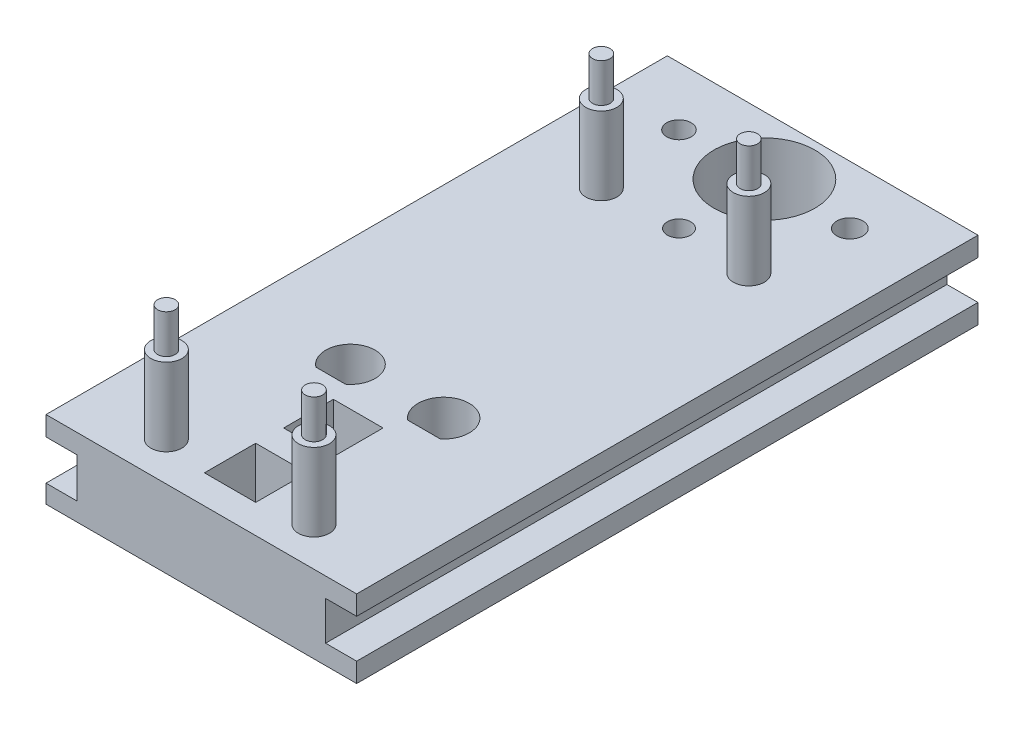
SolidWorks part; units mm, degrees
ref_plane "Plan de face" through (0, 0, 0) normal (0, 0, 1) x (1, 0, 0)
ref_plane "Plan de dessus" through (0, 0, 0) normal (0, 1, 0) x (1, 0, 0)
ref_plane "Plan de droite" through (0, 0, 0) normal (1, 0, 0) x (0, 0, -1)
sketch "Esquisse2" plane through (0, 0, 0) normal (0, 1, 0) x (1, 0, 0)
  line L1 (-20, 40) -> (20, 40)
  line L2 (-20, 40) -> (-20, -40)
  line L3 (-20, -40) -> (20, -40)
  line L4 (20, 40) -> (20, -40)
  line L5 (-20, 40) -> (20, -40) construction
  line L6 (-20, -40) -> (20, 40) construction
  point P0 (0, 0)
  dimension "D1" = 80
  dimension "D2" = 40
extrude "Boss.-Extru.1" add sketch "Esquisse2" along normal blind 10
sketch "Esquisse3" plane through (0, 10, 0) normal (0, 1, 0) x (1, 0, 0)
  line L2 (-20, -40) -> (20, -40) construction
  circle A0 centre (9.5, -35) radius 2
  circle A1 centre (9.5, 21) radius 2
  circle A2 centre (-9.5, -35) radius 2
  circle A3 centre (-9.5, 21) radius 2
  dimension "D3" = 4
  dimension "D5" = 4
  dimension "D7" = 4
  dimension "D8" = 4
  dimension "D1" = 9.5
  dimension "D2" = 5
  dimension "D4" = 56
  dimension "D6" = 19
extrude "Boss.-Extru.2" add sketch "Esquisse3" along normal blind 10
sketch "Esquisse4" plane through (0, 20, 0) normal (0, 1, 0) x (1, 0, 0)
  circle A0 centre (-9.5, -35) radius 1.125
  circle A1 centre (-9.5, -35) radius 2 construction
  circle A2 centre (9.5, -35) radius 1.125
  circle A3 centre (9.5, -35) radius 2 construction
  circle A4 centre (-9.5, 21) radius 1.125
  circle A5 centre (-9.5, 21) radius 2 construction
  circle A6 centre (9.5, 21) radius 1.125
  circle A7 centre (9.5, 21) radius 2 construction
  dimension "D2" = 2.25
  dimension "D3" = 2.25
  dimension "D4" = 2.25
  dimension "D5" = 2.25
  dimension "D1" = 0
extrude "Boss.-Extru.3" add sketch "Esquisse4" along normal blind 5
sketch "Esquisse5" plane through (0, 10, 0) normal (0, 1, 0) x (1, 0, 0)
  line L0 (20, 40) -> (-20, 40) construction
  circle A0 centre (0, 21.5) radius 1.5
  circle A1 centre (-11, 32.5) radius 1.575
  circle A2 centre (11, 32.5) radius 1.675
  circle A3 centre (0, 32.5) radius 6.5
  dimension "D1" = 3
  dimension "D2" = 3.15
  dimension "D3" = 3.35
  dimension "D4" = 13
  dimension "D5" = 7.5
  dimension "D6" = 11
  dimension "D7" = 11
  dimension "D8" = 11
extrude "Enlèv. mat.-Extru.1" cut sketch "Esquisse5" against normal up to next
sketch "Esquisse6" plane through (0, 10, 0) normal (0, 1, 0) x (1, 0, 0)
  line L0 (-20, -40) -> (20, -40) construction
  line L1 (3.3, -36.3) -> (-3.3, -36.3)
  line L2 (3.3, -36.3) -> (3.3, -29.7)
  line L3 (3.3, -29.7) -> (-3.3, -29.7)
  line L4 (-3.3, -36.3) -> (-3.3, -29.7)
  line L5 (3.3, -36.3) -> (-3.3, -29.7) construction
  line L6 (3.3, -29.7) -> (-3.3, -36.3) construction
  line L8 (-3.2, -19.8) -> (3.2, -19.8)
  line L9 (-3.2, -19.8) -> (-3.2, -26.2)
  line L10 (-3.2, -26.2) -> (3.2, -26.2)
  line L11 (3.2, -19.8) -> (3.2, -26.2)
  line L12 (-3.2, -19.8) -> (3.2, -26.2) construction
  line L13 (-3.2, -26.2) -> (3.2, -19.8) construction
  point P0 (0, -33)
  point P8 (0, -23)
  dimension "D1" = 6.6
  dimension "D2" = 7
  dimension "D3" = 6.4
  dimension "D4" = 10
extrude "Enlèv. mat.-Extru.2" cut sketch "Esquisse6" against normal up to next
sketch "Esquisse7" plane through (0, 10, 0) normal (0, 1, 0) x (1, 0, 0)
  line L0 (-7.905, -17.34) -> (-4.095, -17.34)
  line L1 (3.2, -19.8) -> (-3.2, -19.8) construction
  line L2 (3.8901, -17.34) -> (8.1099, -17.34)
  arc A0 (-7.905, -17.34) -> (-4.095, -17.34) centre (-6, -14.8) cw
  arc A1 (3.8901, -17.34) -> (8.1099, -17.34) centre (6, -14.8) cw
  point P2 (-6, -11.625)
  point P10 (6, -11.498)
  dimension "D1" = 3.175
  dimension "D5" = 3.302
  dimension "D2" = 5.715
  dimension "D3" = 5
  dimension "D4" = 6
  dimension "D6" = 5.842
  dimension "D7" = 5
  dimension "D8" = 6
extrude "Enlèv. mat.-Extru.3" cut sketch "Esquisse7" against normal blind 10
sketch "Esquisse8" plane through (0, 0, 40) normal (0, 0, 1) x (1, 0, 0)
  line L0 (20, 10) -> (20, 0) construction
  line L1 (20, 7.5) -> (16, 7.5)
  line L2 (20, 7.5) -> (20, 2.5)
  line L3 (20, 2.5) -> (16, 2.5)
  line L4 (16, 7.5) -> (16, 2.5)
  line L5 (20, 7.5) -> (16, 2.5) construction
  line L6 (20, 2.5) -> (16, 7.5) construction
  line L7 (-20, 10) -> (20, 10) construction
  line L8 (-20, 10) -> (-20, 0) construction
  line L9 (-20, 7.5) -> (-16, 7.5)
  line L10 (-20, 7.5) -> (-20, 2.35)
  line L11 (-20, 2.35) -> (-16, 2.35)
  line L12 (-16, 7.5) -> (-16, 2.35)
  line L13 (-20, 7.5) -> (-16, 2.35) construction
  line L14 (-20, 2.35) -> (-16, 7.5) construction
  point P4 (18, 5)
  point P13 (-18, 4.925)
  dimension "D1" = 2.5
  dimension "D2" = 5
  dimension "D3" = 4
  dimension "D4" = 4
  dimension "D5" = 2.5
  dimension "D6" = 5.15
extrude "Enlèv. mat.-Extru.4" cut sketch "Esquisse8" against normal up to next
